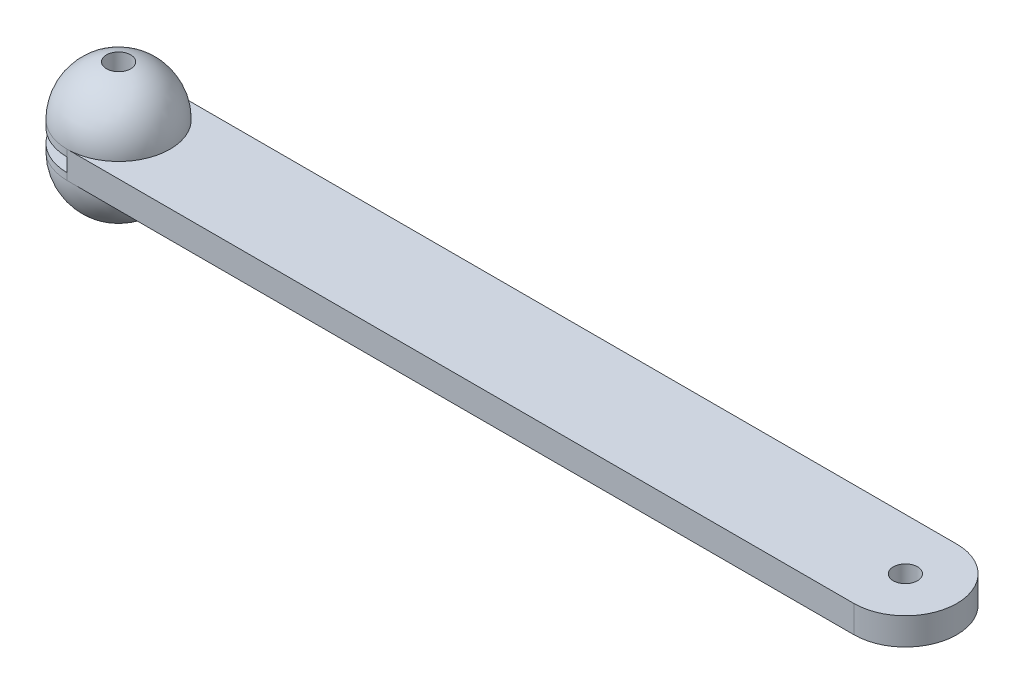
SolidWorks part; units mm, degrees
ref_plane "Plan de face" through (0, 0, 0) normal (0, 0, 1) x (1, 0, 0)
ref_plane "Plan de dessus" through (0, 0, 0) normal (0, 1, 0) x (1, 0, 0)
ref_plane "Plan de droite" through (0, 0, 0) normal (1, 0, 0) x (0, 0, -1)
sketch "Esquisse1" plane through (0, 0, 0) normal (0, 1, 0) x (1, 0, 0)
  line L0 (-232.15, 0) -> (232.15, 0) construction
  line L1 (-232.15, 30.35) -> (232.15, 30.35)
  line L2 (-232.15, -30.35) -> (232.15, -30.35)
  arc A0 (-232.15, 30.35) -> (-232.15, -30.35) centre (-232.15, 0) ccw
  arc A1 (232.15, -30.35) -> (232.15, 30.35) centre (232.15, 0) ccw
  point P2 (0, 0)
  dimension "D1" = 464.3
  dimension "D2" = 60.7
extrude "Boss.-Extru.1" add sketch "Esquisse1" along normal mid plane 16
sketch "Esquisse2" plane through (0, 8, 0) normal (0, 1, 0) x (1, 0, 0)
  circle A0 centre (232.15, 0) radius 7.15
  dimension "D1" = 14.3
extrude "Enlèv. mat.-Extru.1" cut sketch "Esquisse2" against normal through all
sketch "Esquisse3" plane through (0, 8, 0) normal (0, 1, 0) x (1, 0, 0)
  line L0 (232.15, 30.35) -> (-232.15, 30.35) construction
  line L1 (-232.15, 30.35) -> (-232.15, -30.35)
  arc A0 (-232.15, -30.35) -> (-232.15, 30.35) centre (-232.15, 0) cw
revolve "Révolution1" add sketch "Esquisse3" angle 180 about L1
mirror "Symétrie1" about plane through (0, 0, 0) normal (0, 1, 0) of "Révolution1"
sketch "Esquisse4" plane through (0, 0, 0) normal (0, 1, 0) x (1, 0, 0)
  line L0 (0, 0) -> (-232.15, 0) construction
  circle A0 centre (-232.15, 0) radius 30.35
  dimension "D1" = 60.7
  dimension "D2" = 232.15
extrude "Enlèv. mat.-Extru.2" cut sketch "Esquisse4" against normal mid plane 8
sketch "Esquisse5" plane through (0, 0, 0) normal (0, 1, 0) x (1, 0, 0)
  circle A0 centre (-232.15, 0) radius 7.15
  dimension "D1" = 14.3
extrude "Enlèv. mat.-Extru.3" cut sketch "Esquisse5" against normal through all both and the other way through all
